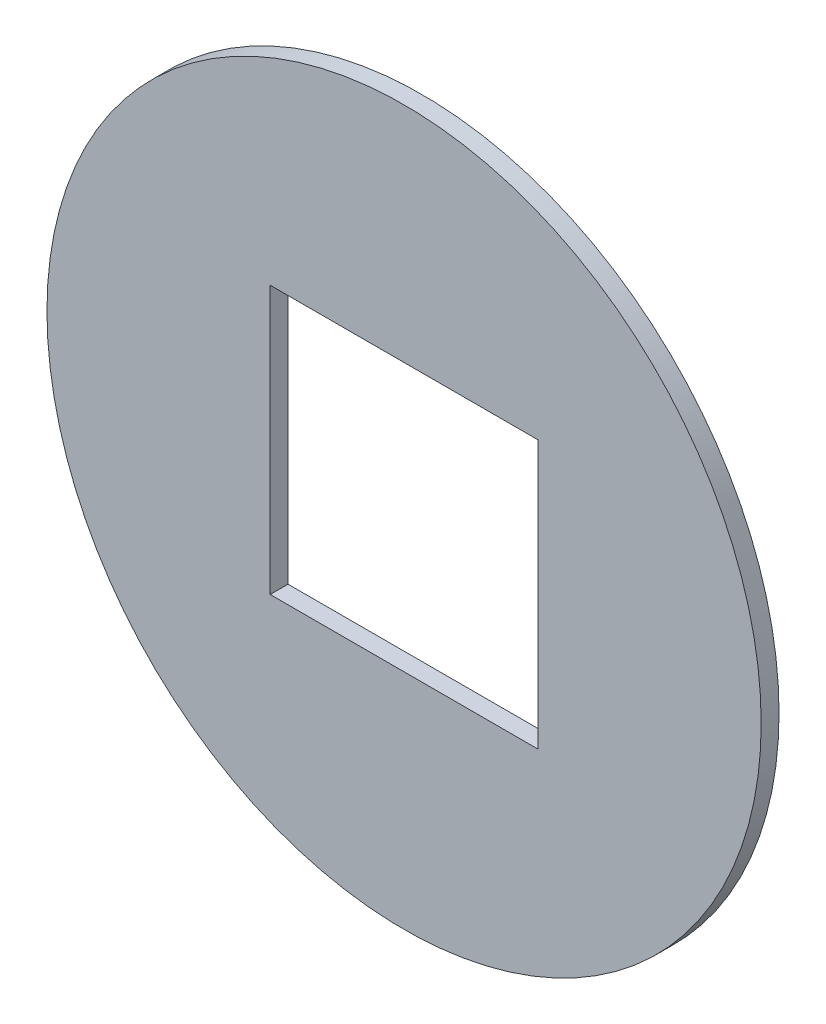
SolidWorks part; units mm, degrees
ref_plane "Front Plane" through (0, 0, 0) normal (0, 0, 1) x (1, 0, 0)
ref_plane "Top Plane" through (0, 0, 0) normal (0, 1, 0) x (1, 0, 0)
ref_plane "Right Plane" through (0, 0, 0) normal (1, 0, 0) x (0, 0, -1)
sketch "Sketch1" plane through (0, 0, 0) normal (0, 0, 1) x (1, 0, 0)
  circle A0 centre (0, 0) radius 10
  dimension "D1" = 20
extrude "Boss-Extrude1" add sketch "Sketch1" along normal blind 0.5
sketch "Sketch2" plane through (0, 0, 0.5) normal (0, 0, 1) x (1, 0, 0)
  line L1 (3.75, 3.75) -> (-3.75, 3.75)
  line L2 (3.75, 3.75) -> (3.75, -3.75)
  line L3 (3.75, -3.75) -> (-3.75, -3.75)
  line L4 (-3.75, 3.75) -> (-3.75, -3.75)
  line L5 (3.75, 3.75) -> (-3.75, -3.75) construction
  line L6 (3.75, -3.75) -> (-3.75, 3.75) construction
  point P0 (0, 0)
  dimension "D1" = 7.5
  dimension "D2" = 7.5
extrude "Boss-Extrude2" add sketch "Sketch2" against normal through all contours L2 L1 L4 L3
sketch "Sketch3" plane through (0, 0, 0.5) normal (0, 0, 1) x (1, 0, 0)
  line L1 (3.75, 3.75) -> (-3.75, 3.75)
  line L2 (3.75, 3.75) -> (3.75, -3.75)
  line L3 (3.75, -3.75) -> (-3.75, -3.75)
  line L4 (-3.75, 3.75) -> (-3.75, -3.75)
  line L5 (3.75, 3.75) -> (-3.75, -3.75) construction
  line L6 (3.75, -3.75) -> (-3.75, 3.75) construction
  point P0 (0, 0)
  dimension "D1" = 7.5
  dimension "D2" = 7.5
extrude "Cut-Extrude1" cut sketch "Sketch3" against normal through all contours L2 L1 L4 L3
